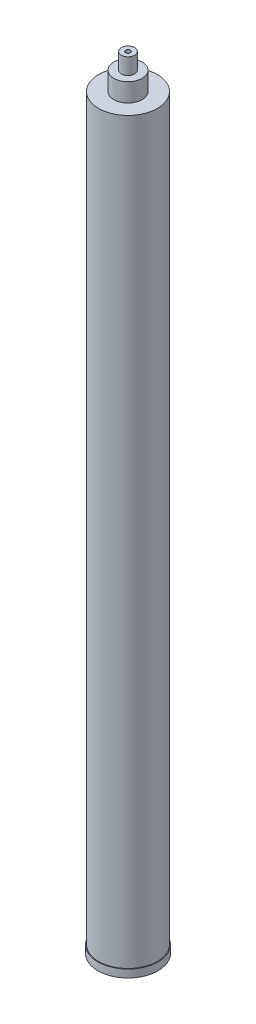
SolidWorks part; units mm, degrees
ref_plane "Front Plane" through (0, 0, 0) normal (0, 0, 1) x (1, 0, 0)
ref_plane "Top Plane" through (0, 0, 0) normal (0, 1, 0) x (1, 0, 0)
ref_plane "Right Plane" through (0, 0, 0) normal (1, 0, 0) x (0, 0, -1)
other "Center of Mass"
sketch "Sketch1" plane through (0, 0, 0) normal (0, 1, 0) x (1, 0, 0)
  circle A0 centre (0, 0) radius 49.25
  dimension "D1" = 98.5
extrude "mainTube" add sketch "Sketch1" along normal blind 1239
sketch "Sketch2" plane through (0, 0, 0) normal (0, -1, 0) x (1, 0, 0)
  circle A0 centre (0, 0) radius 50.45
  circle A1 centre (0, 0) radius 49.25 construction
  dimension "D1" = 1.2
extrude "nozzleRetainer" add sketch "Sketch2" along normal blind 13
sketch "Sketch3" plane through (0, 1239, 0) normal (0, 1, 0) x (1, 0, 0)
  circle A0 centre (0, 0) radius 23.75
  dimension "D1" = 47.5
extrude "mountShoulder" add sketch "Sketch3" along normal blind 31
sketch "Sketch4" plane through (0, 1270, 0) normal (0, 1, 0) x (1, 0, 0)
  circle A0 centre (0, 0) radius 11.125
  dimension "D1" = 22.25
extrude "mountNeck" add sketch "Sketch4" along normal blind 27.2
hole_wizard "3/8-16 Tapped Hole1" positions "Sketch5" profile "Sketch6" tap size "3/8-16" standard "ANSI Inch"
sketch "Sketch5" plane through (0, 1297.2, 0) normal (0, 1, 0) x (1, 0, 0)
  point P0 (0, 0)
sketch "Sketch6" plane through (0, 1297.2, 0) normal (1, 0, 0) x (0, 0, 1)
  line L0 (0, 0) -> (0, 29.6847)
  line L1 (0, 29.6847) -> (3.9687, 27.3)
  line L2 (3.9687, 27.3) -> (3.9687, 0)
  line L5 (3.9687, 0) -> (0, 0)
  line L10 (0, 29.6847) -> (-3.9688, 27.3) construction
  line L11 (0, -6.35) -> (0, 107.95) construction
  dimension "Tap Drill Dia." = 7.9375
  dimension "Tap Drill Depth" = 27.3
  dimension "Drill Angle" = 118
cosmetic thread "Hole Thread2" parameters "D1"=25, "D2"=9.525
sketch "superImportantNotes" plane through (0, 0, 0) normal (0, 0, 1) x (1, 0, 0)
  line L0 (0, -13) -> (82.4152, -140.3539)
  line L1 (-50.45, -13) -> (50.45, -13) construction
  line L2 (89.8745, 1411.3233) -> (89.8745, 1269.2671)
  line L3 (89.8745, 1411.3233) -> (78.8453, 1392.2202)
  line L4 (78.8453, 1392.2202) -> (100.9037, 1392.2202)
  line L5 (100.9037, 1392.2202) -> (89.8745, 1411.3233)
  text T0 "pushy fire" font "Century Gothic" height 20
  text T1 "space" font "Century Gothic" height 20
  text T2 "Positions along the length of the casing can shift by a few millimeters when it's assembled, \r\nso leave some allowances.\r\nAlso, the tube length is what's reported in OpenRocket.\r\nIt still needs to be confirmed against the actual casing." font "Century Gothic" height 20
